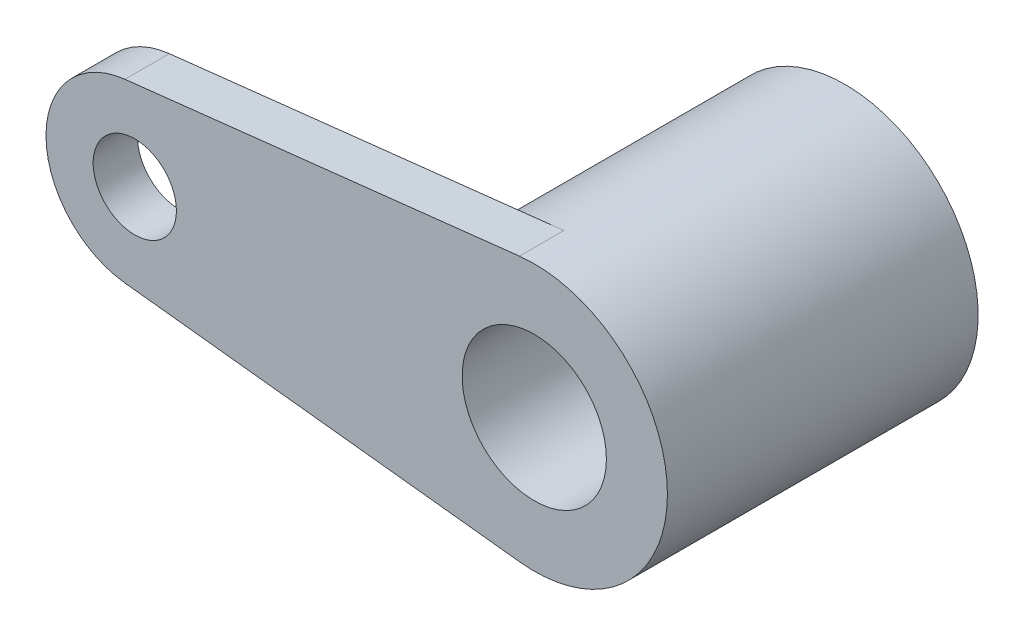
SolidWorks part; units mm, degrees
material "Pine"
ref_plane "Front Plane" through (0, 0, 0) normal (0, 0, 1) x (1, 0, 0)
ref_plane "Top Plane" through (0, 0, 0) normal (0, 1, 0) x (1, 0, 0)
ref_plane "Right Plane" through (0, 0, 0) normal (1, 0, 0) x (0, 0, -1)
other "Configuration Table"
sketch "Sketch1" plane through (0, 0, 0) normal (0, 0, 1) x (1, 0, 0)
  line L0 (-117.1222, -25.2427) -> (-4.2333, -37.8641)
  line L1 (-117.1222, 25.2427) -> (-4.2333, 37.8641)
  line L2 (-114.3, 0) -> (0, 0) construction
  circle A0 centre (-114.3, 0) radius 25.4
  circle A1 centre (0, 0) radius 38.1
  dimension "D1" = 76.2
  dimension "D2" = 50.8
  dimension "D3" = 114.3
extrude "Boss-Extrude1" add sketch "Sketch1" along normal blind 12.7
hole_wizard "CBORE for #0 Binding Head Machine Screw1" positions "Sketch3" profile "Sketch4" counterbore size "#0" standard "ANSI Inch" end condition through all
sketch "Sketch3" plane through (0, 0, 12.7) normal (0, 0, 1) x (1, 0, 0)
  point P0 (-114.3, 0)
sketch "Sketch4" plane through (-114.3, 0, 12.7) normal (1, 0, 0) x (0, -1, 0)
  line L0 (0, 0) -> (0, 12.7)
  line L1 (0, 12.7) -> (7.9375, 12.7)
  line L3 (7.9375, 12.7) -> (7.9375, 15.875)
  line L4 (7.9375, 15.875) -> (11.9126, 15.875)
  line L5 (11.9126, 15.875) -> (11.9126, 0)
  line L7 (11.9126, 0) -> (0, 0)
  line L11 (0, -6.35) -> (0, 107.95) construction
  dimension "Thru Hole Dia." = 15.875
  dimension "Thru Hole Depth" = 12.7
  dimension "C'Bore Dia." = 23.8252
  dimension "C'Bore Depth" = 15.875
hole_wizard "CSK for 3/8 Flat Head Machine Screw (100)2" [suppressed] positions "Sketch7" profile "Sketch8" countersink size "3/8" standard "ANSI Inch"
sketch "Sketch7" plane through (0, 0, 0) normal (0, 0, -1) x (-1, 0, 0)
  point P0 (0, 0)
sketch "Sketch8" plane through (0, 0, 0) normal (1, 0, 0) x (0, 1, 0)
  line L0 (0, 0) -> (0, 12.7)
  line L1 (0, 12.7) -> (5.0419, 12.7)
  line L2 (5.0419, 12.7) -> (5.0419, 3.8896)
  line L3 (5.0419, 3.8896) -> (9.6774, 0)
  line L5 (9.6774, 0) -> (0, 0)
  line L6 (-5.0419, 3.8896) -> (-9.6774, 0) construction
  line L11 (0, -6.35) -> (0, 107.95) construction
  dimension "Thru Hole Dia." = 10.0838
  dimension "Thru Hole Depth" = 12.7
  dimension "Near C'Sink Dia." = 19.3548
  dimension "Near C'Sink Angle" = 100
sketch "Sketch2" plane through (0, 0, 12.7) normal (0, 0, 1) x (1, 0, 0)
  circle A0 centre (-114.3, 0) radius 8.255
  dimension "D1" = 16.51
extrude "Cut-Extrude1" [suppressed] cut sketch "Sketch2" against normal blind 5.715
sketch "Sketch9" plane through (0, 0, 12.7) normal (0, 0, 1) x (1, 0, 0)
  circle A0 centre (0, 0) radius 20.6375
  dimension "D1" = 41.275
extrude "Cut-Extrude2" cut sketch "Sketch9" against normal through all
sketch "Sketch10" plane through (0, 0, 12.7) normal (0, 0, 1) x (1, 0, 0)
  line L0 (0, 0) -> (-174.0223, 0)
sketch "Sketch11" plane through (0, 0, 0) normal (0, 0, -1) x (-1, 0, 0)
  circle A0 centre (0, 0) radius 38.1
  circle A1 centre (0, 0) radius 20.6375 construction
  circle A2 centre (0, 0) radius 20.6375
  dimension "D1" = 76.2
extrude "Boss-Extrude2" add sketch "Sketch11" along normal blind 76.2
